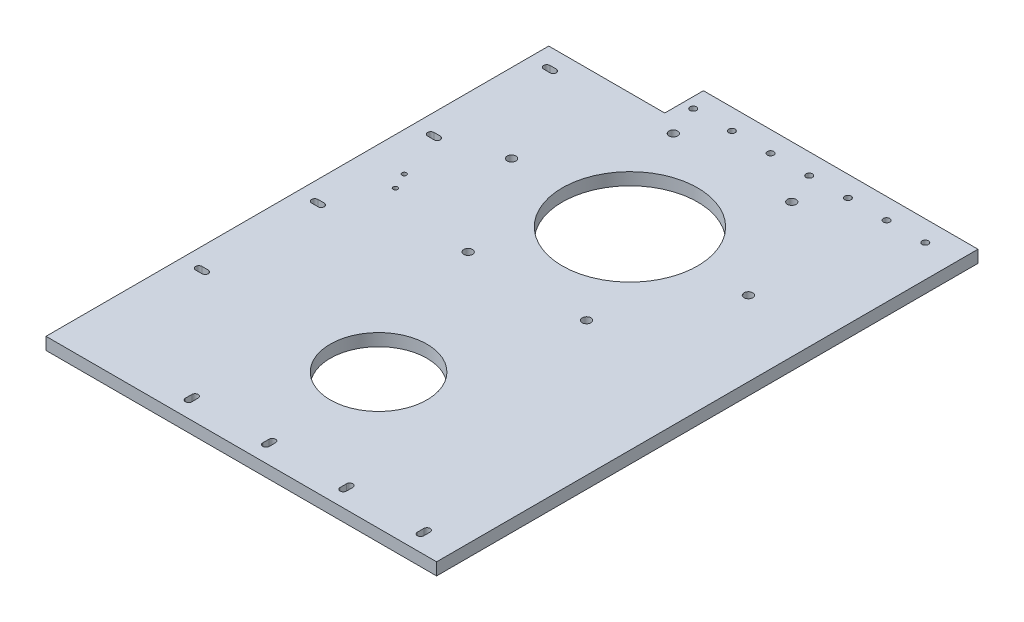
SolidWorks part; units mm, degrees
ref_plane "Front Plane" through (0, 0, 0) normal (0, 0, 1) x (1, 0, 0)
ref_plane "Top Plane" through (0, 0, 0) normal (0, 1, 0) x (1, 0, 0)
ref_plane "Right Plane" through (0, 0, 0) normal (1, 0, 0) x (0, 0, -1)
sketch "Sketch1" plane through (0, 0, 0) normal (0, 1, 0) x (1, 0, 0)
  line L3 (-71, 140) -> (71, 140)
  line L4 (71, -140) -> (71, 140)
  line L5 (0, 140) -> (0, -135) construction
  line L6 (0, 0) -> (71, 0) construction
  line L10 (-71, 140) -> (-71, 120)
  line L11 (-71, 120) -> (-131, 120)
  line L12 (-131, 120) -> (-131, -140)
  line L13 (-131, -140) -> (71, -140)
  point P0 (0, 0)
  dimension "D1" = 280
  dimension "D2" = 20
  dimension "D3" = 202
  dimension "D4" = 60
extrude "Boss-Extrude1" add sketch "Sketch1" along normal blind 6.35
sketch "Sketch2" plane through (0, 6.35, 0) normal (0, 1, 0) x (1, 0, 0)
  line L1 (0, 140) -> (0, -140) construction
  line L2 (71, 140) -> (-71, 140) construction
  line L3 (-131, -140) -> (71, -140) construction
  circle A0 centre (0, -65) radius 41.5 construction
  circle A1 centre (0, -23.5) radius 2.25
  circle A2 centre (29.3449, -35.6551) radius 2.25
  circle A3 centre (41.5, -65) radius 2.25
  circle A4 centre (29.3449, -94.3449) radius 2.25
  circle A5 centre (0, -106.5) radius 2.25
  circle A6 centre (-29.3449, -94.3449) radius 2.25
  circle A7 centre (-41.5, -65) radius 2.25
  circle A8 centre (-29.3449, -35.6551) radius 2.25
  circle A9 centre (0, -65) radius 80 construction
  circle A10 centre (0, -65) radius 30
  point P22 (0, -65)
  dimension "D1" = 83
  dimension "D2" = 4.5
  dimension "D4" = 160
  dimension "D6" = 60
  dimension "D5" = 75
  dimension "D3" = 8
extrude "Cut-Extrude1" [suppressed] cut sketch "Sketch2" against normal through all
sketch "Sketch6" [suppressed] plane through (0, 6.35, 0) normal (0, 1, 0) x (1, 0, 0)
  line L0 (0, -65) -> (-38.9712, -46.8274) construction
  line L1 (0, -65) -> (0, -23.5) construction
  line L2 (-40.9787, -51.1324) -> (-36.9638, -42.5225) construction
  line L3 (-36.9638, -42.5225) -> (-27.9007, -46.7486) construction
  circle A0 centre (0, -65) radius 30 construction
  circle A1 centre (-36.9638, -42.5225) radius 0.85
  circle A2 centre (-40.9787, -51.1324) radius 0.85
  circle A5 centre (-29.9082, -51.0536) radius 0.85
  point P7 (-38.9712, -46.8274)
  dimension "D4" = 1.7
  dimension "D5" = 10
  dimension "D7" = 10
  dimension "D6" = 1.7
  dimension "D1" = 43
  dimension "D2" = 9.5
  dimension "D3" = 65
extrude "Cut-Extrude5" [suppressed] cut sketch "Sketch6" against normal through all
sketch "Sketch8" [suppressed] plane through (0, 6.35, 0) normal (0, 1, 0) x (1, 0, 0)
  line L1 (71, 140) -> (-71, 140) construction
  line L2 (65, -20.6305) -> (65, 140) construction
  line L3 (71, -140) -> (71, 140) construction
  line L5 (45, 41.8036) -> (45, 140) construction
  circle A0 centre (0, 65) radius 25
  circle A1 centre (0, -65) radius 30 construction
  dimension "D1" = 130
  dimension "D2" = 50
  dimension "D3" = 6
  dimension "D4" = 20
extrude "Cut-Extrude9" [suppressed] cut sketch "Sketch8" against normal through all
sketch "Sketch9" plane through (0, 0, 0) normal (0, -1, 0) x (-1, 0, 0)
  circle A1 centre (45.6, 129.325) radius 1.65
  circle A2 centre (5.6, 129.325) radius 1.65
  circle A3 centre (-34.4, 129.325) radius 1.65
  circle A4 centre (65.6, 129.325) radius 1.65
  circle A5 centre (25.6, 129.325) radius 1.65
  circle A6 centre (-14.4, 129.325) radius 1.65
  circle A7 centre (-54.4, 129.325) radius 1.65
extrude "Cut-Extrude10" cut sketch "Sketch9" against normal blind 30
sketch "Sketch10" plane through (0, 0, 0) normal (0, -1, 0) x (1, 0, 0)
  line L0 (-121.975, 10) -> (-118.675, 10) construction
  line L3 (-121.975, 11.65) -> (-118.675, 11.65)
  line L4 (-121.975, 8.35) -> (-118.675, 8.35)
  line L5 (-121.975, 70) -> (-118.675, 70) construction
  line L6 (-121.975, 71.65) -> (-118.675, 71.65)
  line L7 (-121.975, 68.35) -> (-118.675, 68.35)
  line L8 (-121.975, -50) -> (-118.675, -50) construction
  line L9 (-121.975, -48.35) -> (-118.675, -48.35)
  line L10 (-121.975, -51.65) -> (-118.675, -51.65)
  line L11 (-121.975, -110) -> (-118.675, -110) construction
  line L12 (-121.975, -108.35) -> (-118.675, -108.35)
  line L13 (-121.975, -111.65) -> (-118.675, -111.65)
  circle A0 centre (-120.325, -110) radius 1.65
  circle A1 centre (-120.325, -50) radius 1.65
  circle A2 centre (-120.325, 10) radius 1.65
  circle A3 centre (-120.325, 70) radius 1.65
  arc A6 (-121.975, 11.65) -> (-121.975, 8.35) centre (-121.975, 10) ccw
  arc A7 (-118.675, 8.35) -> (-118.675, 11.65) centre (-118.675, 10) ccw
  arc A8 (-121.975, 71.65) -> (-121.975, 68.35) centre (-121.975, 70) ccw
  arc A9 (-118.675, 68.35) -> (-118.675, 71.65) centre (-118.675, 70) ccw
  arc A10 (-121.975, -48.35) -> (-121.975, -51.65) centre (-121.975, -50) ccw
  arc A11 (-118.675, -51.65) -> (-118.675, -48.35) centre (-118.675, -50) ccw
  arc A12 (-121.975, -108.35) -> (-121.975, -111.65) centre (-121.975, -110) ccw
  arc A13 (-118.675, -111.65) -> (-118.675, -108.35) centre (-118.675, -110) ccw
  point P14 (-120.325, 10)
  point P21 (-120.325, 70)
  point P28 (-120.325, -50)
  point P35 (-120.325, -110)
  dimension "D1" = 3.3
  dimension "D2" = 3.3
  dimension "D3" = 3.3
  dimension "D4" = 3.3
  dimension "D5" = 1.65
  dimension "D6" = 1.65
  dimension "D7" = 1.65
  dimension "D8" = 1.65
sketch "Sketch11" plane through (0, 6.35, 0) normal (0, 1, 0) x (1, 0, 0)
  line L0 (71, -127.15) -> (-131, -127.15) construction
  line L1 (71, -140) -> (71, 140) construction
  line L2 (456.625, -127.15) -> (-127.825, -127.15) construction
  line L3 (-131, 120) -> (-131, -140) construction
  line L4 (71, -132.85) -> (-131, -132.85) construction
  line L5 (456.625, -132.85) -> (-127.825, -132.85) construction
  line L6 (-65.6, 129.325) -> (-65.6, -130.005) construction
  line L7 (-65.6, -130.005) -> (71, -130) construction
  line L8 (456.625, -130) -> (-127.825, -130) construction
  line L9 (-25.6, 129.325) -> (-25.6, -130.0035) construction
  line L10 (14.4, 129.325) -> (14.4, -130.0021) construction
  line L11 (54.4, 129.325) -> (54.4, -130.0006) construction
  line L12 (-65.6, -128.355) -> (-65.6, -131.655) construction
  line L13 (-63.95, -128.355) -> (-63.95, -131.655)
  line L14 (-67.25, -128.355) -> (-67.25, -131.655)
  line L15 (-25.6, -128.3535) -> (-25.6, -131.6535) construction
  line L16 (-23.95, -128.3535) -> (-23.95, -131.6535)
  line L17 (-27.25, -128.3535) -> (-27.25, -131.6535)
  line L18 (14.4, -128.3521) -> (14.4, -131.6521) construction
  line L19 (16.05, -128.3521) -> (16.05, -131.6521)
  line L20 (12.75, -128.3521) -> (12.75, -131.6521)
  line L21 (54.4, -128.3506) -> (54.4, -131.6506) construction
  line L22 (56.05, -128.3506) -> (56.05, -131.6506)
  line L23 (52.75, -128.3506) -> (52.75, -131.6506)
  circle A0 centre (-65.6, -130.005) radius 1.65 construction
  circle A1 centre (-25.6, -130.0035) radius 1.65 construction
  circle A2 centre (14.4, -130.0021) radius 1.65 construction
  circle A3 centre (54.4, -130.0006) radius 1.65 construction
  arc A4 (-63.95, -128.355) -> (-67.25, -128.355) centre (-65.6, -128.355) ccw
  arc A5 (-67.25, -131.655) -> (-63.95, -131.655) centre (-65.6, -131.655) ccw
  arc A6 (-23.95, -128.3535) -> (-27.25, -128.3535) centre (-25.6, -128.3535) ccw
  arc A7 (-27.25, -131.6535) -> (-23.95, -131.6535) centre (-25.6, -131.6535) ccw
  arc A8 (16.05, -128.3521) -> (12.75, -128.3521) centre (14.4, -128.3521) ccw
  arc A9 (12.75, -131.6521) -> (16.05, -131.6521) centre (14.4, -131.6521) ccw
  arc A10 (56.05, -128.3506) -> (52.75, -128.3506) centre (54.4, -128.3506) ccw
  arc A11 (52.75, -131.6506) -> (56.05, -131.6506) centre (54.4, -131.6506) ccw
  point P33 (-65.6, -130.005)
  point P39 (-25.6, -130.0035)
  point P46 (14.4, -130.0021)
  point P53 (54.4, -130.0006)
  dimension "D2" = 3.3
  dimension "D1" = 259.33
extrude "Cut-Extrude12" cut sketch "Sketch11" against normal blind 30
extrude "Cut-Extrude13" cut sketch "Sketch10" against normal blind 10 contours A0 | L13 A13 L12 A0 | L12 A12 L13 A0 | L9 A10 L10 A1 | A1 | L10 A11 L9 A1 | L3 A6 L4 A2 | A2 | L4 A7 L3 A2 | L6 A8 L7 A3 | A3 | L7 A9 L6 A3
sketch "Sketch12" plane through (0, 6.35, 0) normal (0, 1, 0) x (1, 0, 0)
  line L0 (-131, -140) -> (71, -140) construction
  line L1 (71, -140) -> (71, 140) construction
  circle A0 centre (-29, 60) radius 35
  dimension "D1" = 70
  dimension "D2" = 200
  dimension "D3" = 100
extrude "Cut-Extrude14" cut sketch "Sketch12" against normal through all
sketch "Sketch13" plane through (0, 6.35, 0) normal (0, 1, 0) x (1, 0, 0)
  line L0 (-96.5, 60) -> (-84, 60) construction
  circle A2 centre (-29, 60) radius 67.5 construction
  circle A3 centre (-90.25, 60) radius 2.25
  circle A4 centre (-59.625, 113.0441) radius 2.25
  circle A5 centre (-29, 60) radius 67.5 construction
  circle A6 centre (1.625, 113.0441) radius 2.25
  circle A7 centre (-29, 60) radius 67.5 construction
  circle A8 centre (32.25, 60) radius 2.25
  circle A9 centre (-29, 60) radius 67.5 construction
  circle A10 centre (1.625, 6.9559) radius 2.25
  circle A11 centre (-29, 60) radius 67.5 construction
  circle A12 centre (-59.625, 6.9559) radius 2.25
  circle A13 centre (-29, 60) radius 67.5 construction
  circle A14 centre (-29, 60) radius 55 construction
  circle A15 centre (-29, 60) radius 35 construction
  point P25 (-29, 60)
  dimension "D1" = 135
  dimension "D2" = 4.5
  dimension "D3" = 6
  dimension "D4" = 110
extrude "Cut-Extrude15" cut sketch "Sketch13" against normal through all
sketch "Sketch14" plane through (0, 6.35, 0) normal (0, 1, 0) x (1, 0, 0)
  circle A0 centre (-29, -70) radius 25
  circle A1 centre (-29, 60) radius 35 construction
  circle A2 centre (-29, 60) radius 35 construction
  dimension "D1" = 50
  dimension "D2" = 130
extrude "Cut-Extrude16" cut sketch "Sketch14" against normal blind 10
sketch "Sketch15" plane through (0, 6.35, 0) normal (0, 1, 0) x (1, 0, 0)
  line L0 (-111.0245, 25.2989) -> (-106.9837, 16.7011) construction
  line L1 (-94.5, -140) -> (-94.5, 120) construction
  line L2 (-131, 120) -> (-131, -140) construction
  line L3 (-71, 120) -> (-131, 120) construction
  line L4 (-131, -140) -> (71, -140) construction
  line L5 (-94.5, 26) -> (-131, 26) construction
  line L6 (-94.5, 16) -> (-131, 16) construction
  line L7 (-131, 26) -> (-131, 16) construction
  line L8 (-99.1997, 26) -> (-94.5, 16) construction
  circle A0 centre (-111.0245, 25.2989) radius 1.175
  circle A1 centre (-106.9837, 16.7011) radius 1.175
  circle A2 centre (-29, 60) radius 78 construction
  circle A3 centre (-29, 60) radius 35 construction
  point P18 (-109.0041, 21)
  point P19 (-131, 21)
  point P23 (0, 0)
  point P24 (0, 0)
  dimension "D1" = 2.35
  dimension "D2" = 9.5
  dimension "D3" = 11
  dimension "D7" = 156
  dimension "D4" = 36.5
  dimension "D5" = 94
  dimension "D6" = 10
extrude "Cut-Extrude17" cut sketch "Sketch15" against normal blind 10
